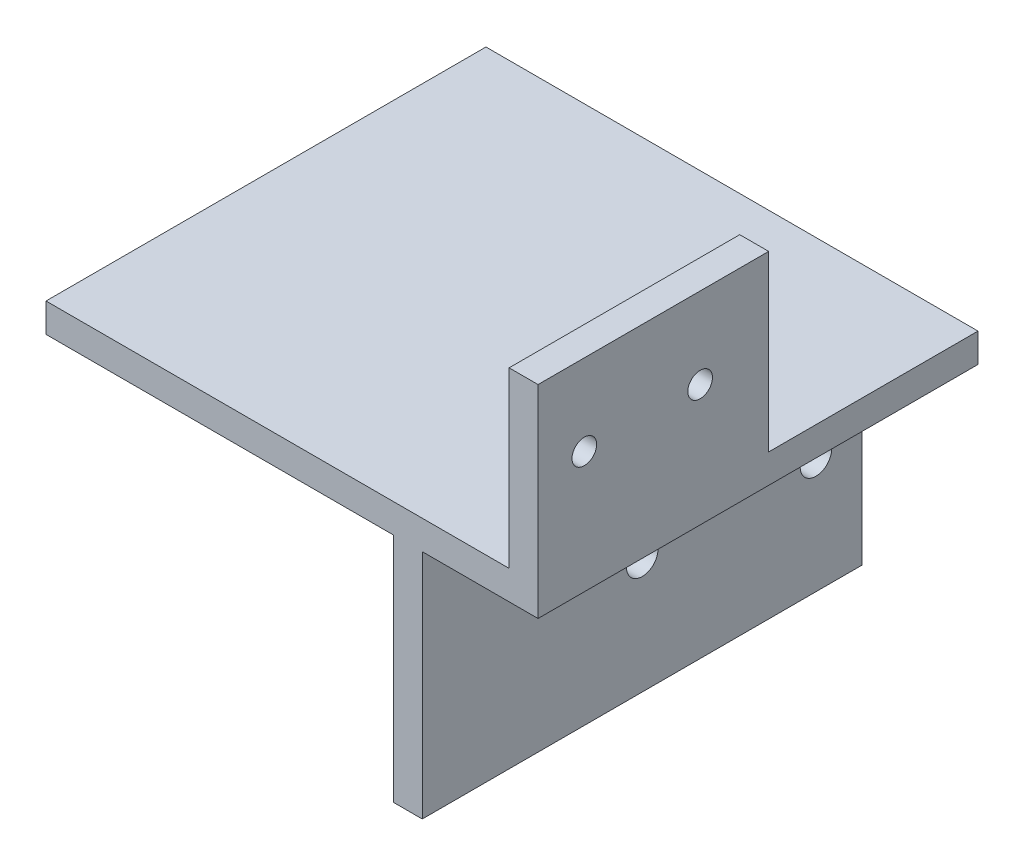
SolidWorks part; units mm, degrees
ref_plane "Front Plane" through (0, 0, 0) normal (0, 0, 1) x (1, 0, 0)
ref_plane "Top Plane" through (0, 0, 0) normal (0, 1, 0) x (1, 0, 0)
ref_plane "Right Plane" through (0, 0, 0) normal (1, 0, 0) x (0, 0, -1)
sketch "Sketch1" plane through (0, 0, 0) normal (0, 0, 1) x (1, 0, 0)
  line L0 (15.875, 28.575) -> (-38.1, 28.575)
  line L1 (-38.1, 28.575) -> (-38.1, 25.4)
  line L2 (15.875, 28.575) -> (15.875, 25.4)
  line L3 (15.875, 25.4) -> (3.175, 25.4)
  line L4 (3.175, 25.4) -> (3.175, 0)
  line L5 (3.175, 0) -> (0, 0)
  line L6 (-38.1, 25.4) -> (0, 25.4)
  line L7 (0, 25.4) -> (0, 0)
  dimension "D1" = 3.175
  dimension "D2" = 3.175
  dimension "D3" = 53.975
  dimension "D4" = 38.1
  dimension "D5" = 25.4
extrude "Boss-Extrude1" add sketch "Sketch1" along normal blind 48.26
sketch "Sketch2" plane through (0, 28.575, 0) normal (0, 1, 0) x (1, 0, 0)
  line L1 (15.875, -48.26) -> (12.7, -48.26)
  line L2 (15.875, -48.26) -> (15.875, -22.9611)
  line L3 (15.875, -22.9611) -> (12.7, -22.9611)
  line L4 (12.7, -48.26) -> (12.7, -22.9611)
  dimension "D1" = 25.2989
  dimension "D2" = 3.175
extrude "Boss-Extrude2" add sketch "Sketch2" along normal blind 19.05
hole_wizard "Tap Drill for #6-32 Tap1" positions "Sketch4" profile "Sketch3" hole size "#6-32" standard "ANSI Inch" end condition through all
sketch "Sketch4" plane through (15.875, 0, 0) normal (1, 0, 0) x (0, 0, -1)
  line L0 (-48.26, 25.4) -> (-48.26, 47.625) construction
  line L1 (-48.26, 47.625) -> (-22.9611, 47.625) construction
  point P0 (-43.18, 38.735)
  point P2 (-30.48, 38.735)
  dimension "D1" = 12.7
  dimension "D2" = 5.08
  dimension "D3" = 8.89
sketch "Sketch3" plane through (15.875, 38.735, 43.18) normal (0, 1, 0) x (0, 0, -1)
  line L0 (0, 0) -> (0, 53.975)
  line L1 (0, 53.975) -> (1.3525, 53.975)
  line L2 (1.3525, 53.975) -> (1.3525, 0)
  line L5 (1.3525, 0) -> (0, 0)
  line L11 (0, -6.35) -> (0, 107.95) construction
  dimension "Thru Hole Dia." = 2.7051
  dimension "Thru Hole Depth" = 53.975
hole_wizard "Tap Drill for #8-32 Tap1" positions "Sketch6" profile "Sketch5" hole size "#8-32" standard "ANSI Inch" end condition through all
sketch "Sketch6" plane through (0, 0, 0) normal (-1, 0, 0) x (0, 0, 1)
  line L0 (0, 25.4) -> (0, 0) construction
  line L1 (48.26, 0) -> (0, 0) construction
  point P0 (5.08, 12.7)
  point P2 (24.13, 12.7)
  dimension "D1" = 19.05
  dimension "D3" = 5.08
  dimension "D4" = 12.7
sketch "Sketch5" plane through (0, 12.7, 5.08) normal (0, 1, 0) x (0, 0, 1)
  line L0 (0, 0) -> (0, 15.875)
  line L1 (0, 15.875) -> (1.7272, 15.875)
  line L2 (1.7272, 15.875) -> (1.7272, 0)
  line L5 (1.7272, 0) -> (0, 0)
  line L11 (0, -6.35) -> (0, 107.95) construction
  dimension "Thru Hole Dia." = 3.4544
  dimension "Thru Hole Depth" = 15.875
